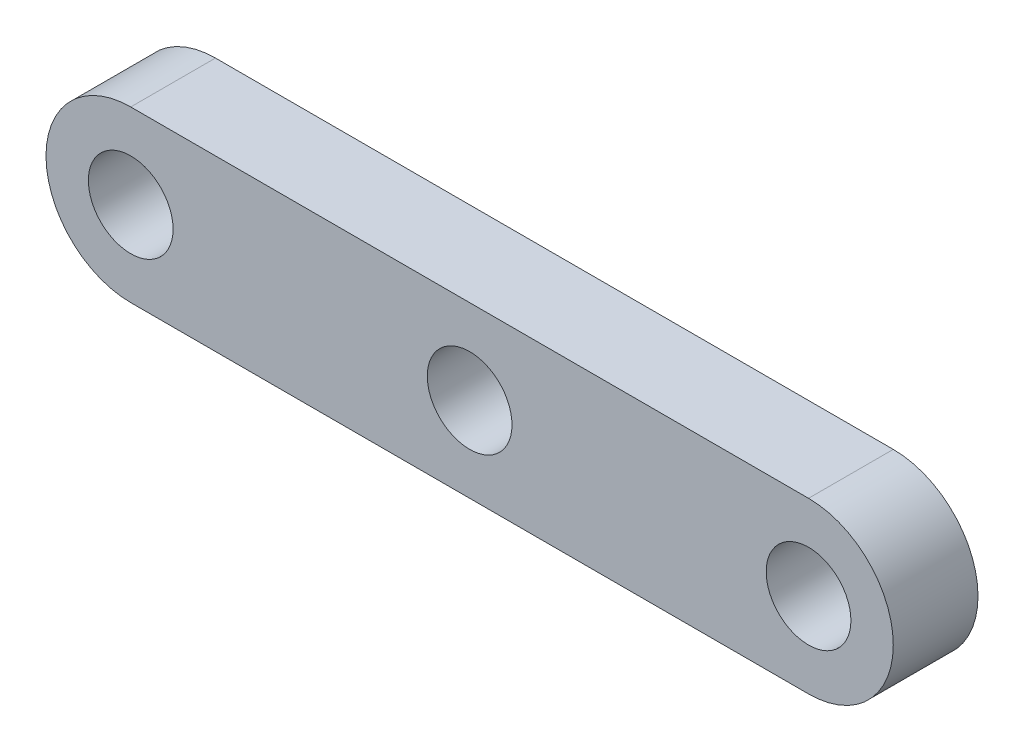
SolidWorks part; units mm, degrees
material "ABS"
ref_plane "Front Plane" through (0, 0, 0) normal (0, 0, 1) x (1, 0, 0)
ref_plane "Top Plane" through (0, 0, 0) normal (0, 1, 0) x (1, 0, 0)
ref_plane "Right Plane" through (0, 0, 0) normal (1, 0, 0) x (0, 0, -1)
sketch "Sketch2" plane through (0, 0, 0) normal (0, 0, 1) x (1, 0, 0)
  line L0 (25.4, 0) -> (-25.4, 0) construction
  line L1 (25.4, -6.35) -> (-25.4, -6.35)
  line L2 (25.4, 6.35) -> (-25.4, 6.35)
  arc A0 (25.4, -6.35) -> (25.4, 6.35) centre (25.4, 0) ccw
  arc A1 (-25.4, 6.35) -> (-25.4, -6.35) centre (-25.4, 0) ccw
  point P2 (0, 0)
  dimension "D1" = 50.8
  dimension "D2" = 12.7
extrude "Boss-Extrude1" add sketch "Sketch2" along normal blind 6.35
sketch "Sketch3" plane through (0, 0, 6.35) normal (0, 0, 1) x (1, 0, 0)
  circle A0 centre (-25.4, 0) radius 3.175
  circle A1 centre (0, 0) radius 3.175
  circle A2 centre (25.4, 0) radius 3.175
  dimension "D1" = 6.35
  dimension "D2" = 6.35
  dimension "D3" = 6.35
extrude "Cut-Extrude1" cut sketch "Sketch3" against normal through all
